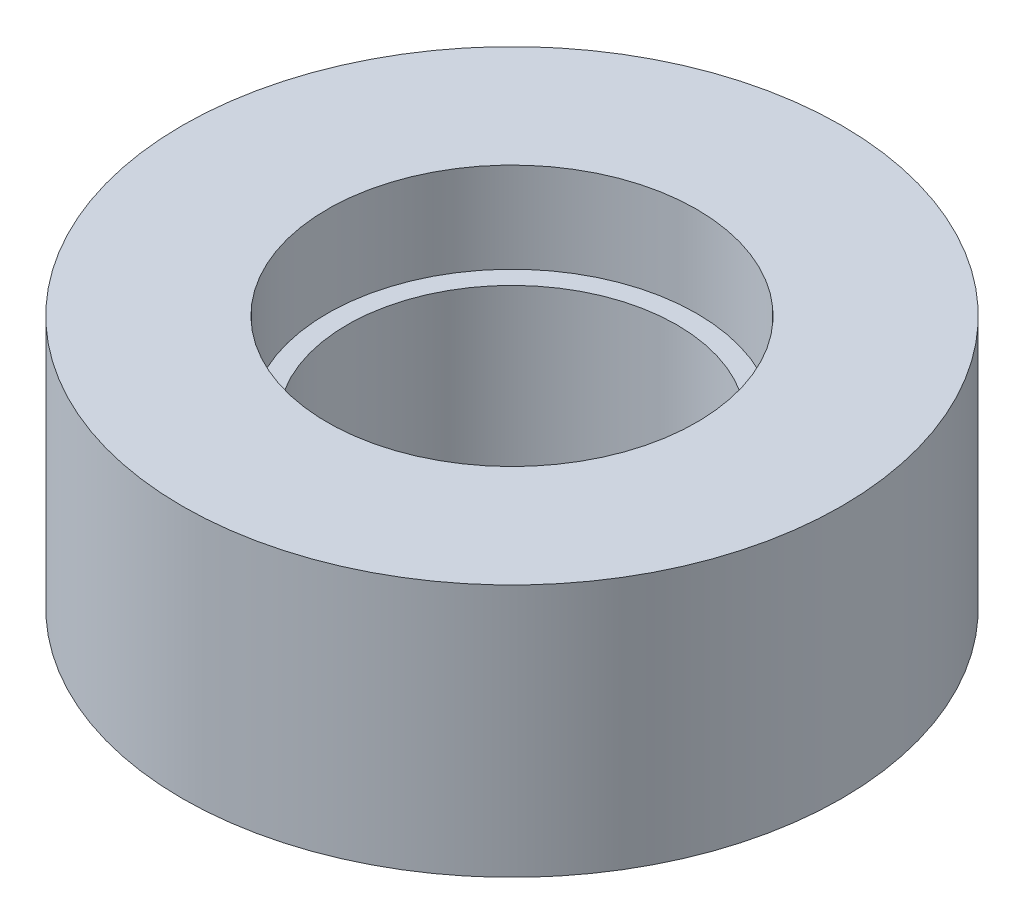
SolidWorks part; units mm, degrees
material "ABS"
ref_plane "Front Plane" through (0, 0, 0) normal (0, 0, 1) x (1, 0, 0)
ref_plane "Top Plane" through (0, 0, 0) normal (0, 1, 0) x (1, 0, 0)
ref_plane "Right Plane" through (0, 0, 0) normal (1, 0, 0) x (0, 0, -1)
sketch "Sketch1" plane through (0, 0, 0) normal (1, 0, 0) x (0, 0, -1)
  line L0 (0, 0) -> (0, 14.9191) construction
  line L1 (-8.89, 12.192) -> (-8.89, 7.8486)
  line L2 (-8.89, 7.8486) -> (-7.9375, 7.8486)
  line L3 (-7.9375, 7.8486) -> (-7.9375, 0)
  line L7 (-15.875, 0) -> (-15.875, 12.192)
  line L8 (-15.875, 12.192) -> (-8.89, 12.192)
  line L9 (-15.875, 0) -> (-7.9375, 0)
  dimension "D1" = 17.78
  dimension "D2" = 7.9375
  dimension "D3" = 12.192
  dimension "D4" = 7.8486
  dimension "D5" = 31.75
revolve "Revolve1" add sketch "Sketch1" angle 360 about L0
